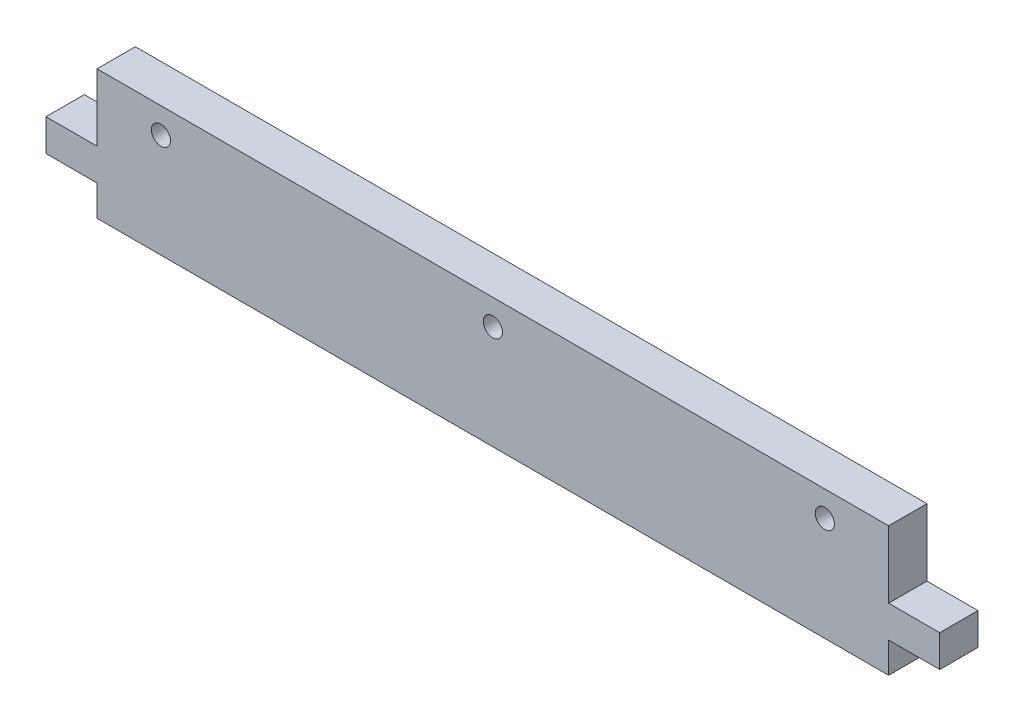
SolidWorks part; units mm, degrees
ref_plane "前视基准面" through (0, 0, 0) normal (0, 0, 1) x (1, 0, 0)
ref_plane "上视基准面" through (0, 0, 0) normal (0, 1, 0) x (1, 0, 0)
ref_plane "右视基准面" through (0, 0, 0) normal (1, 0, 0) x (0, 0, -1)
sketch "草图1" plane through (0, 0, 0) normal (0, 0, 1) x (1, 0, 0)
  line L1 (0, 0) -> (124, 0)
  line L2 (0, 0) -> (0, 20.28)
  line L3 (0, 20.28) -> (124, 20.28)
  line L4 (124, 0) -> (124, 20.28)
  dimension "D1" = 20.28
  dimension "D2" = 124
extrude "凸台-拉伸1" add sketch "草图1" along normal blind 6
sketch "草图2" plane through (0, 0, 6) normal (0, 0, 1) x (1, 0, 0)
  line L0 (0, 7.28) -> (-11.8027, 7.28) construction
  line L1 (0, 20.28) -> (0, 0) construction
  line L2 (62, 20.28) -> (62, 0) construction
  line L3 (0, 9.78) -> (-8, 9.78)
  line L4 (0, 9.78) -> (0, 4.78)
  line L5 (0, 4.78) -> (-8, 4.78)
  line L6 (-8, 9.78) -> (-8, 4.78)
  line L7 (124, 20.28) -> (0, 20.28) construction
  line L8 (0, 0) -> (124, 0) construction
  line L9 (124, 7.28) -> (135.8027, 7.28) construction
  line L10 (132, 9.78) -> (132, 4.78)
  line L11 (124, 4.78) -> (132, 4.78)
  line L12 (124, 9.78) -> (124, 4.78)
  line L13 (124, 9.78) -> (132, 9.78)
  line L15 (124, 20.28) -> (0, 20.28) construction
  dimension "D1" = 8
  dimension "D2" = 2.5
  dimension "D3" = 5
  dimension "D4" = 13
extrude "凸台-拉伸2" add sketch "草图2" against normal blind 6
sketch "草图3" plane through (0, 0, 0) normal (0, 0, -1) x (-1, 0, 0)
  line L0 (-62, 20.28) -> (-62, 0) construction
  line L1 (-124, 20.28) -> (0, 20.28) construction
  line L2 (0, 0) -> (-124, 0) construction
  line L3 (-124, 16.28) -> (0, 16.28) construction
  line L4 (-124, 0) -> (-124, 4.78) construction
  line L5 (0, 4.78) -> (0, 0) construction
  circle A0 centre (-62, 16.28) radius 1.5
  circle A1 centre (-114, 16.28) radius 1.5
  circle A2 centre (-10, 16.28) radius 1.5
  dimension "D2" = 3
  dimension "D3" = 3
  dimension "D1" = 4
  dimension "D4" = 52
extrude "切除-拉伸1" cut sketch "草图3" against normal through all
